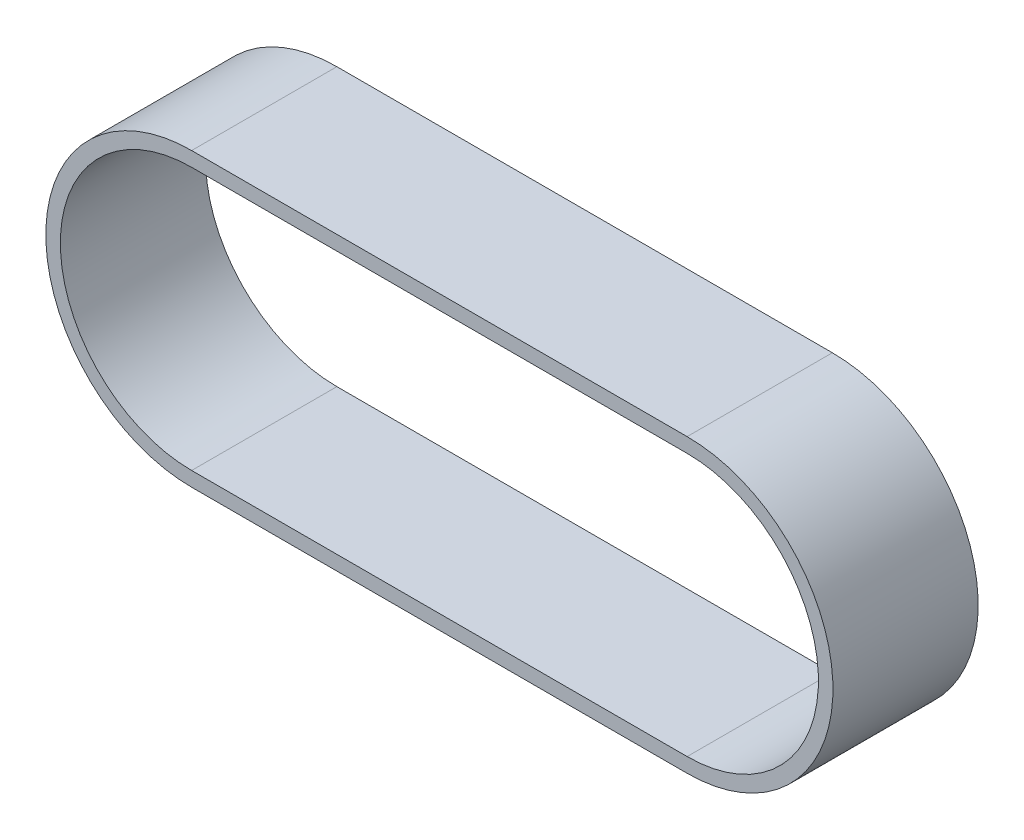
SolidWorks part; units mm, degrees
ref_plane "Vorne" through (0, 0, 0) normal (0, 0, 1) x (1, 0, 0)
ref_plane "Oben" through (0, 0, 0) normal (0, 1, 0) x (1, 0, 0)
ref_plane "Rechts" through (0, 0, 0) normal (1, 0, 0) x (0, 0, -1)
sketch "Skizze1" plane through (0, 0, 0) normal (0, 0, 1) x (1, 0, 0)
  line L0 (55, 0) -> (-55, 0) construction
  line L1 (0, 4.52) -> (17.06, 4.52)
  line L2 (0, -4.52) -> (17.06, -4.52)
  line L3 (0, -55) -> (0, 55) construction
  line L4 (0, 5.02) -> (17.06, 5.02)
  line L5 (0, -5.02) -> (17.06, -5.02)
  arc A0 (0, 4.52) -> (0, -4.52) centre (0, 0) ccw
  arc A1 (17.06, -4.52) -> (17.06, 4.52) centre (17.06, 0) ccw
  arc A2 (17.06, -5.02) -> (17.06, 5.02) centre (17.06, 0) ccw
  arc A3 (0, 5.02) -> (0, -5.02) centre (0, 0) ccw
  dimension "D1" = 9.04
  dimension "D2" = 17.06
  dimension "D3" = 0.5
extrude "Aufsatz-Linear austragen1" add sketch "Skizze1" along normal mid plane 5
